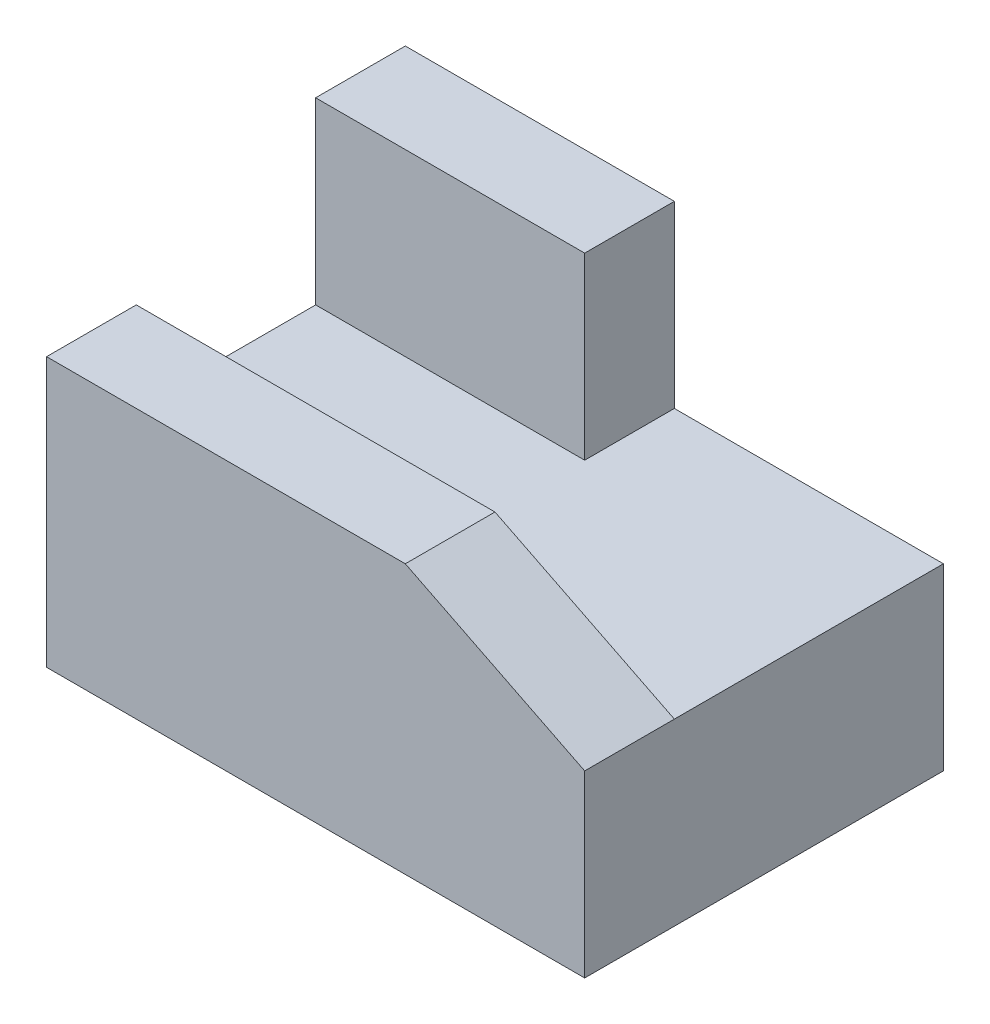
SolidWorks part; units mm, degrees
ref_plane "Front Plane" through (0, 0, 0) normal (0, 0, 1) x (1, 0, 0)
ref_plane "Top Plane" through (0, 0, 0) normal (0, 1, 0) x (1, 0, 0)
ref_plane "Right Plane" through (0, 0, 0) normal (1, 0, 0) x (0, 0, -1)
sketch "Sketch1" plane through (0, 0, 0) normal (0, 1, 0) x (1, 0, 0)
  line L1 (-30, 20) -> (30, 20)
  line L2 (-30, 20) -> (-30, -20)
  line L3 (-30, -20) -> (30, -20)
  line L4 (30, 20) -> (30, -20)
  line L5 (-30, 20) -> (30, -20) construction
  line L6 (-30, -20) -> (30, 20) construction
  point P0 (0, 0)
  dimension "D1" = 40
  dimension "D2" = 60
extrude "Boss-Extrude1" add sketch "Sketch1" along normal blind 20
sketch "Sketch2" plane through (0, 0, 20) normal (0, 0, 1) x (1, 0, 0)
  line L0 (-30, 20) -> (-30, 30)
  line L1 (-30, 30) -> (10, 30)
  line L2 (10, 30) -> (30, 20)
  line L3 (30, 20) -> (-30, 20)
  dimension "D1" = 10
  dimension "D2" = 20
extrude "Boss-Extrude2" add sketch "Sketch2" against normal blind 10 contours L1 L2 L3 L0
sketch "Sketch3" plane through (0, 0, -20) normal (0, 0, -1) x (-1, 0, 0)
  line L1 (30, 20) -> (0, 20)
  line L2 (30, 20) -> (30, 40)
  line L3 (30, 40) -> (0, 40)
  line L4 (0, 20) -> (0, 40)
  dimension "D1" = 20
  dimension "D2" = 30
extrude "Boss-Extrude3" add sketch "Sketch3" against normal blind 10 contours L2 L3 L4 L1
